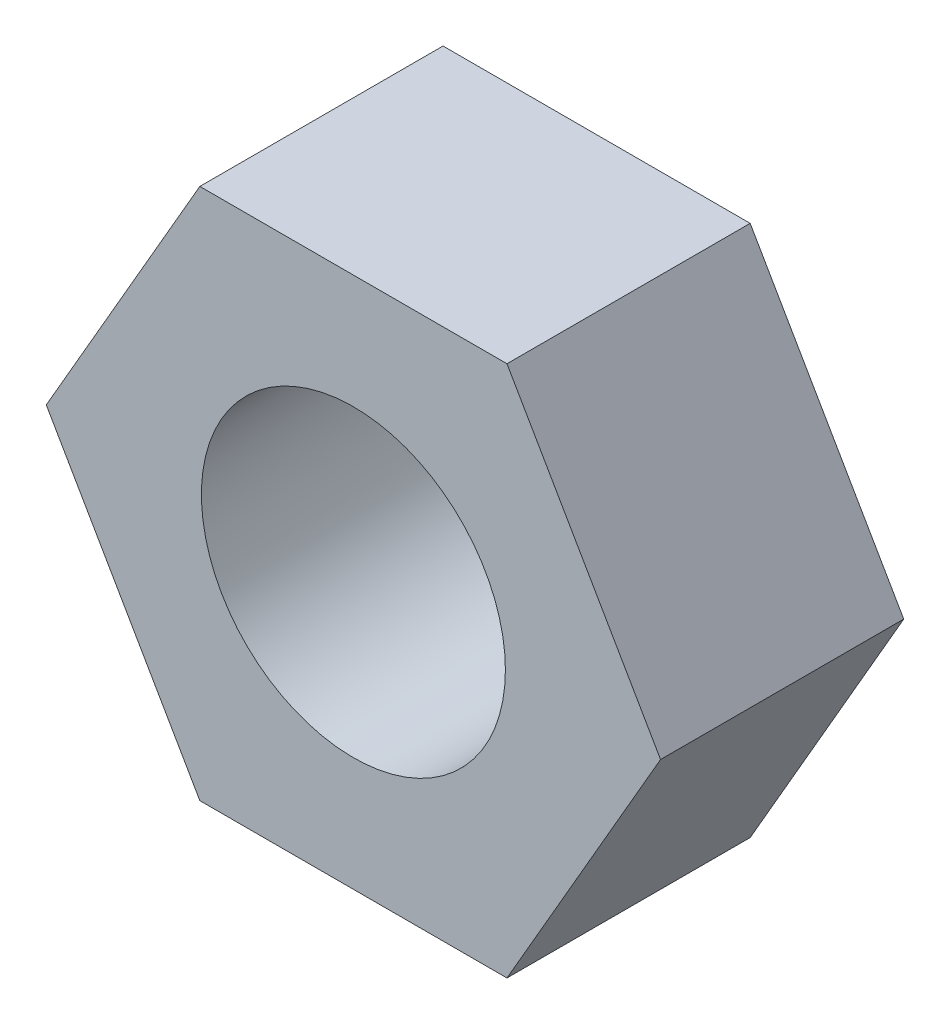
SolidWorks part; units mm, degrees
ref_plane "前视基准面" through (0, 0, 0) normal (0, 0, 1) x (1, 0, 0)
ref_plane "上视基准面" through (0, 0, 0) normal (0, 1, 0) x (1, 0, 0)
ref_plane "右视基准面" through (0, 0, 0) normal (1, 0, 0) x (0, 0, -1)
other "Configuration Table"
sketch "草图1" plane through (0, 0, 0) normal (0, 0, 1) x (1, 0, 0)
  line L0 (4.0415, 0) -> (2.0207, 3.5)
  line L1 (2.0207, 3.5) -> (-2.0207, 3.5)
  line L2 (-2.0207, 3.5) -> (-4.0415, 0)
  line L3 (-4.0415, 0) -> (-2.0207, -3.5)
  line L4 (-2.0207, -3.5) -> (2.0207, -3.5)
  line L5 (2.0207, -3.5) -> (4.0415, 0)
  circle A0 centre (0, 0) radius 2
extrude "标准对边_厚度_螺纹孔" add sketch "草图1" along normal blind 3.2
